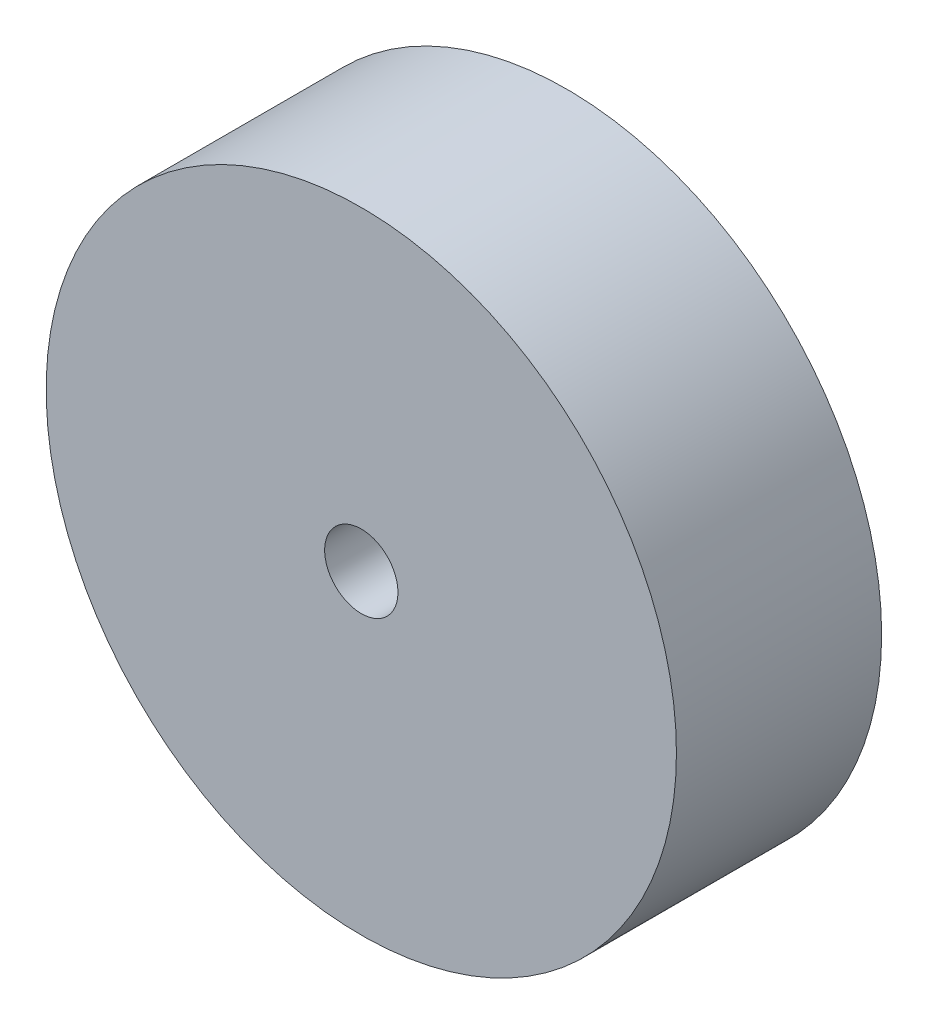
SolidWorks part; units mm, degrees
ref_plane "Front Plane" through (0, 0, 0) normal (0, 0, 1) x (1, 0, 0)
ref_plane "Top Plane" through (0, 0, 0) normal (0, 1, 0) x (1, 0, 0)
ref_plane "Right Plane" through (0, 0, 0) normal (1, 0, 0) x (0, 0, -1)
sketch "Sketch1" plane through (0, 0, 0) normal (0, 0, 1) x (1, 0, 0)
  circle A0 centre (0, 0) radius 21.5
  circle A1 centre (0, 0) radius 2.5
  dimension "D1" = 43
  dimension "D2" = 5
extrude "Boss-Extrude1" add sketch "Sketch1" along normal blind 14
